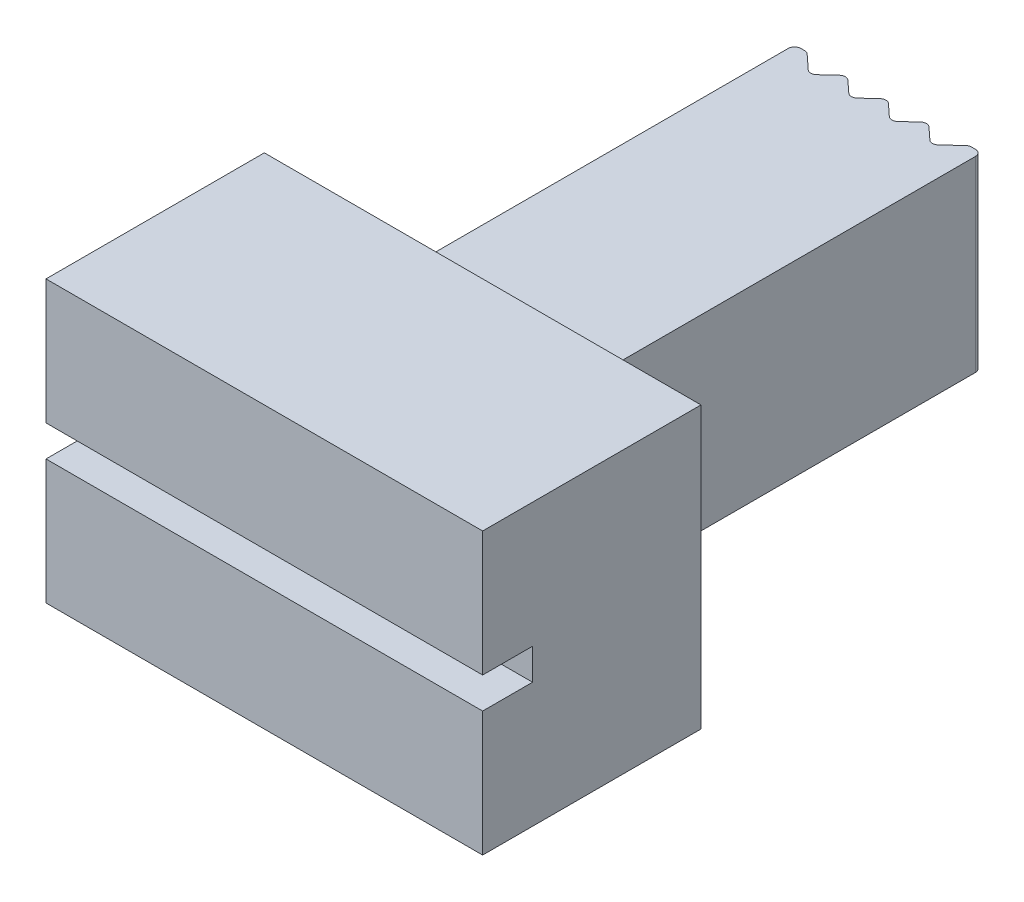
SolidWorks part; units mm, degrees
ref_plane "前视基准面" through (0, 0, 0) normal (0, 0, 1) x (1, 0, 0)
ref_plane "上视基准面" through (0, 0, 0) normal (0, 1, 0) x (1, 0, 0)
ref_plane "右视基准面" through (0, 0, 0) normal (1, 0, 0) x (0, 0, -1)
sketch "草图1" plane through (0, 0, 0) normal (0, 0, 1) x (1, 0, 0)
  line L1 (3.5, -2.25) -> (-3.5, -2.25)
  line L2 (3.5, -2.25) -> (3.5, 2.25)
  line L3 (3.5, 2.25) -> (-3.5, 2.25)
  line L4 (-3.5, -2.25) -> (-3.5, 2.25)
  line L5 (3.5, -2.25) -> (-3.5, 2.25) construction
  line L6 (3.5, 2.25) -> (-3.5, -2.25) construction
  point P0 (0, 0)
  dimension "D1" = 4.5
  dimension "D2" = 7
extrude "凸台-拉伸1" add sketch "草图1" along normal blind 3.5
sketch "草图3" plane through (0, 0, 0) normal (0, 0, -1) x (-1, 0, 0)
  line L1 (1.5, -1.5) -> (-1.5, -1.5)
  line L2 (1.5, -1.5) -> (1.5, 1.5)
  line L3 (1.5, 1.5) -> (-1.5, 1.5)
  line L4 (-1.5, -1.5) -> (-1.5, 1.5)
  line L5 (1.5, -1.5) -> (-1.5, 1.5) construction
  line L6 (1.5, 1.5) -> (-1.5, -1.5) construction
  point P0 (0, 0)
  dimension "D1" = 3
extrude "凸台-拉伸2" add sketch "草图3" along normal blind 6.5
sketch "草图4" plane through (3.5, 0, 0) normal (1, 0, 0) x (0, 0, -1)
  line L0 (-3.5, -2.25) -> (-3.5, 2.25) construction
  line L1 (-4.3, -0.25) -> (-2.7, -0.25)
  line L2 (-4.3, -0.25) -> (-4.3, 0.25)
  line L3 (-4.3, 0.25) -> (-2.7, 0.25)
  line L4 (-2.7, -0.25) -> (-2.7, 0.25)
  line L5 (-4.3, -0.25) -> (-2.7, 0.25) construction
  line L6 (-4.3, 0.25) -> (-2.7, -0.25) construction
  point P0 (-3.5, 0)
  dimension "D1" = 0.5
  dimension "D2" = 0.8
extrude "切除-拉伸1" cut sketch "草图4" against normal through all
sketch "草图5" plane through (0, 1.5, 0) normal (0, 1, 0) x (1, 0, 0)
  line L0 (-1.3, 6.5) -> (-0.975, 6.2)
  line L1 (-1.5, 6.5) -> (1.5, 6.5) construction
  line L2 (-0.975, 6.2) -> (-0.65, 6.5)
  line L3 (-0.65, 6.5) -> (-0.325, 6.2)
  line L4 (-0.325, 6.2) -> (0, 6.5)
  line L5 (0, 6.5) -> (0.325, 6.2)
  line L6 (0.325, 6.2) -> (0.65, 6.5)
  line L7 (0.65, 6.5) -> (0.975, 6.2)
  line L8 (0.975, 6.2) -> (1.3, 6.5)
  line L9 (1.3, 6.5) -> (-1.3, 6.5)
  line L10 (-1.5, 6.5) -> (-1.5, 0) construction
  line M12 (1.5, 6.5) -> (-1.5, 6.5)
  dimension "D1" = 0.2
  dimension "D2" = 0.3
extrude "切除-拉伸2" cut sketch "草图5" against normal blind 6.5 contours L0 L2 M12 | L3 L4 M12 | L5 L6 M12 | L7 L8 M12
fillet "圆角1" radius 0.1 11 edges at (1.5, 0, -6.5) (-1.5, 0, -6.5) (-1.3, 0, -6.5) (1.3, 0, -6.5) (0.975, 0, -6.2) (0.65, 0, -6.5) (0.325, 0, -6.2) (0, 0, -6.5) (-0.325, 0, -6.2) (-0.65, 0, -6.5) (-0.975, 0, -6.2)
